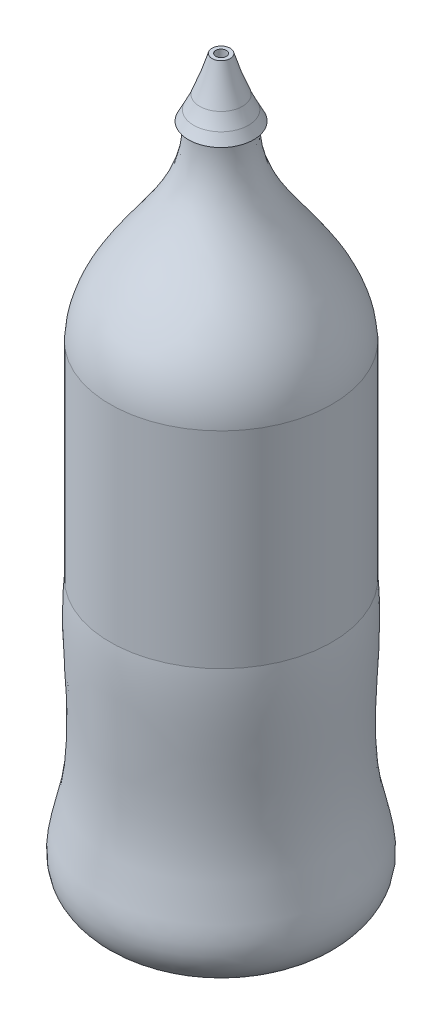
SolidWorks part; units mm, degrees
ref_plane "Front Plane" through (0, 0, 0) normal (0, 0, 1) x (1, 0, 0)
ref_plane "Top Plane" through (0, 0, 0) normal (0, 1, 0) x (1, 0, 0)
ref_plane "Right Plane" through (0, 0, 0) normal (1, 0, 0) x (0, 0, -1)
sketch "Sketch1" plane through (0, 0, 0) normal (0, 0, 1) x (1, 0, 0)
  line L0 (0, 0) -> (0, 320)
  line L2 (52.5675, 229.9372) -> (52.5675, 132.3234)
  line L3 (0, 0) -> (44.2879, 0)
  line L4 (0, 320) -> (0, 331.0542)
  line L5 (0, 331.0542) -> (13, 331.0542)
  line L6 (13, 331.0542) -> (13, 321.577)
  line L7 (13, 321.577) -> (15.4335, 320)
  line L8 (15.4335, 320) -> (13, 320)
  spline S0 degree 3 poles (13, 320) (11.8781, 283.2783) (50.722, 265.4753) (52.5675, 229.9372) knots 0 0 0 0 1 1 1 1
  spline S1 degree 3 poles (52.5675, 132.3234) (55.2455, 101.8801) (44.2481, 56.6014) (64.9974, 10.7682) (44.2879, 0) knots 0 0 0 0 0.662491 1 1 1 1
  dimension "D1" = 320
  dimension "D2" = 13
revolve "Revolve1" add sketch "Sketch1" angle 360 about L0
sketch "Sketch2" plane through (0, 0, 0) normal (0, 0, 1) x (1, 0, 0)
  line L0 (0, 331.0542) -> (0, 357.6596) construction
  line L1 (13, 331.0542) -> (-13, 331.0542) construction
  line L2 (4.2804, 347.7579) -> (0, 347.7579)
  line L3 (0, 347.7579) -> (0, 320)
  line L4 (-13, 320) -> (13, 320) construction
  line L5 (0, 320) -> (15.4335, 320)
  arc A0 (15.4335, 320) -> (4.2804, 347.7579) centre (133.3837, 383.5116) cw
revolve "Revolve2" add sketch "Sketch2" angle 360 about L3
sketch "Sketch3" plane through (0, 0, 0) normal (0, 0, 1) x (1, 0, 0)
  line L0 (13, 331.0542) -> (-13, 331.0542) construction
  line L1 (9.919, 331.0542) -> (13, 331.0542)
  line L2 (13, 331.0542) -> (13, 324.743)
  line L3 (0, 331.0542) -> (0, 352.1154) construction
  arc A0 (13, 324.743) -> (9.919, 331.0542) centre (70.6696, 356.8036) cw
revolve "Cut-Revolve1" cut sketch "Sketch3" angle 360 about L3
sketch "Sketch4" plane through (0, 347.7579, 0) normal (0, 1, 0) x (1, 0, 0)
  circle A0 centre (0, 0) radius 2.5
  dimension "D1" = 5
extrude "Cut-Extrude1" cut sketch "Sketch4" against normal blind 10
